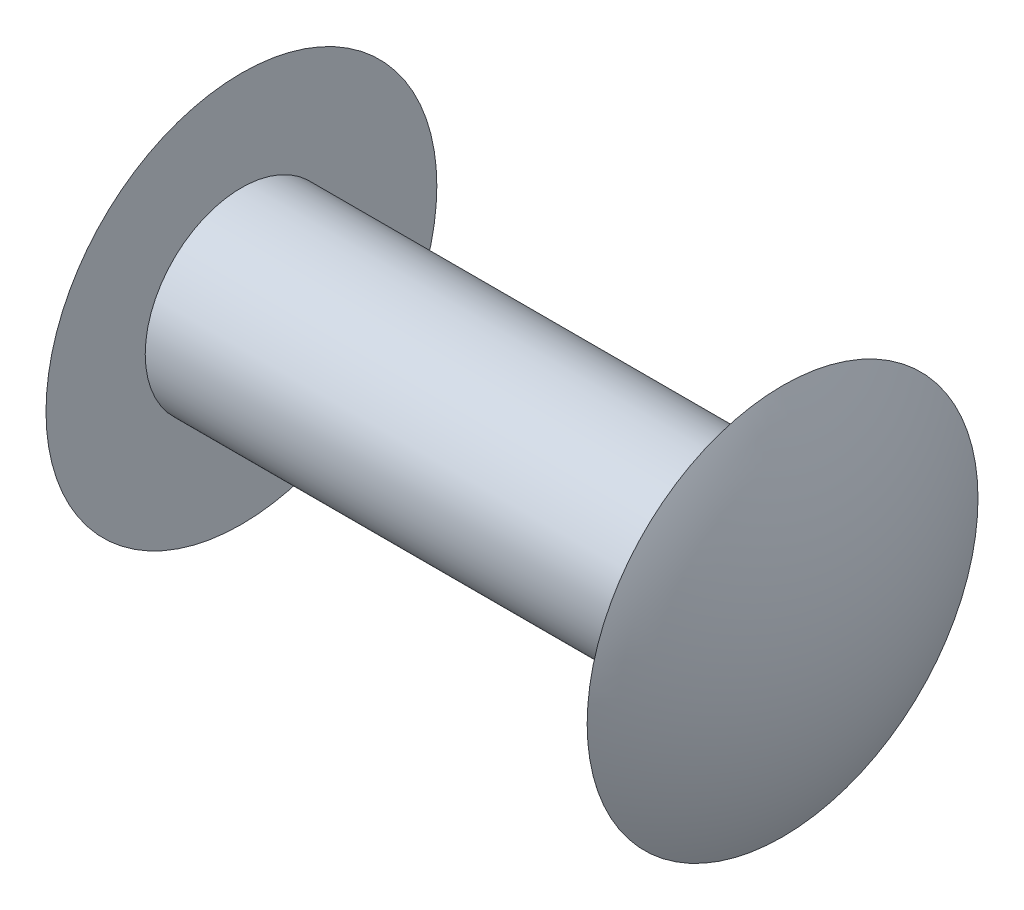
SolidWorks part; units mm, degrees
ref_plane "Front Plane" through (0, 0, 0) normal (0, 0, 1) x (1, 0, 0)
ref_plane "Top Plane" through (0, 0, 0) normal (0, 1, 0) x (1, 0, 0)
ref_plane "Right Plane" through (0, 0, 0) normal (1, 0, 0) x (0, 0, -1)
sketch "Sketch1" plane through (0, 0, 0) normal (0, 0, 1) x (1, 0, 0)
  line L0 (8.7535, 0) -> (-8.7535, 0) construction
  line L1 (0, 3.25) -> (0, 1.6)
  line L2 (0, 1.6) -> (9, 1.6)
  line L3 (9, 1.6) -> (9, 3.25)
  line L4 (-0.8, 0) -> (9.8, 0)
  arc A0 (0, 3.25) -> (-0.8, 0) centre (6.2016, 0) ccw
  arc A1 (9, 3.25) -> (9.8, 0) centre (2.7984, 0) cw
  point P4 (0, 0)
  dimension "D1" = 6.5
  dimension "D2" = 3.2
  dimension "D3" = 9
  dimension "D4" = 0.8
revolve "Revolve1" add sketch "Sketch1" angle 360 about L0
equation "\"d\"=0.003200"
equation "\"L\"=0.009000"
equation "\"D2@Sketch1\"=\"d\"*1000"
equation "\"D3@Sketch1\"=\"L\"*1000"
equation "\"Ls\"=0.009000"
